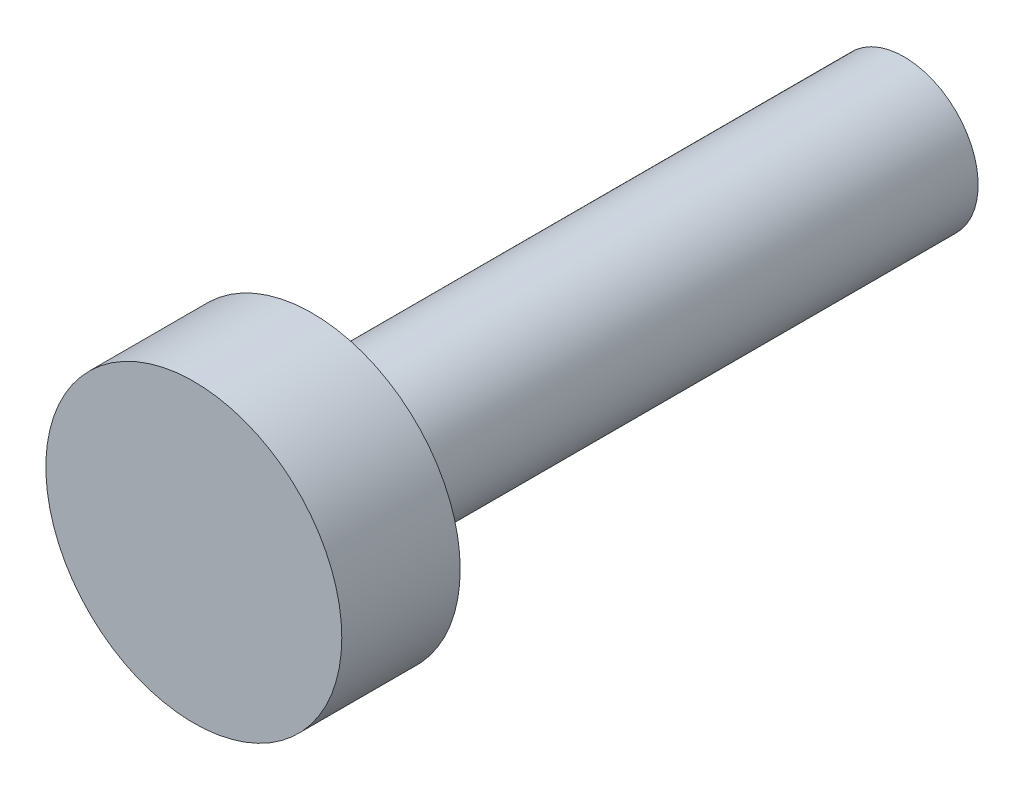
SolidWorks part; units mm, degrees
ref_plane "Plan de face" through (0, 0, 0) normal (0, 0, 1) x (1, 0, 0)
ref_plane "Plan de dessus" through (0, 0, 0) normal (0, 1, 0) x (1, 0, 0)
ref_plane "Plan de droite" through (0, 0, 0) normal (1, 0, 0) x (0, 0, -1)
sketch "Esquisse1" plane through (0, 0, 0) normal (0, 0, 1) x (1, 0, 0)
  circle A0 centre (0, 0) radius 2
  dimension "D1" = 4
extrude "Boss.-Extru.1" add sketch "Esquisse1" along normal blind 1.6
sketch "Esquisse2" plane through (0, 0, 0) normal (0, 0, -1) x (-1, 0, 0)
  circle A0 centre (0, 0) radius 1
  dimension "D1" = 2
extrude "Boss.-Extru.2" add sketch "Esquisse2" along normal blind 8
